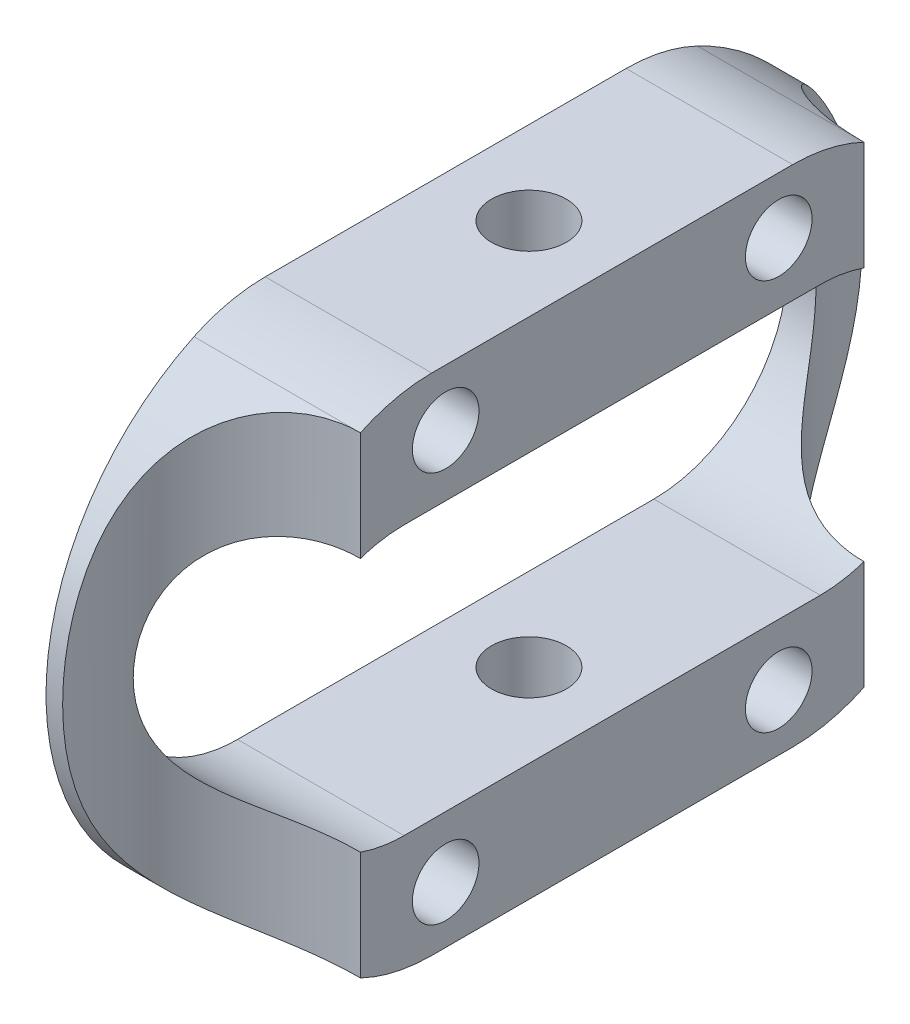
SolidWorks part; units mm, degrees
ref_plane "Płaszczyzna przednia" through (0, 0, 0) normal (0, 0, 1) x (1, 0, 0)
ref_plane "Płaszczyzna górna" through (0, 0, 0) normal (0, 1, 0) x (1, 0, 0)
ref_plane "Płaszczyzna prawa" through (0, 0, 0) normal (1, 0, 0) x (0, 0, -1)
sketch "Szkic1" plane through (0, 0, 0) normal (1, 0, 0) x (0, 0, -1)
  line L0 (25, -16.1572) -> (-25, -16.1572)
  line L1 (0, 16.1572) -> (0, -16.1572) construction
  line L2 (-41, 0) -> (41, 0) construction
  line L3 (25, 16.1572) -> (-25, 16.1572)
  line L4 (-25, -16.1572) -> (25, -16.1572)
  line L5 (-21.6718, -30.2948) -> (21.6718, -30.2948)
  line L6 (21.6718, 30.2948) -> (-21.6718, 30.2948)
  circle A0 centre (-20, 23.5) radius 4
  circle A1 centre (20, 23.5) radius 4
  circle A2 centre (-20, -23.5) radius 4
  circle A3 centre (20, -23.5) radius 4
  ellipse E0 centre (-25, 0) end of major axis (-25, 16.1572) minor radius 16 (-25, 16.1572) -> (-25, -16.1572) ccw
  ellipse E1 centre (25, 0) end of major axis (25, 16.1572) minor radius 16 (25, -16.1572) -> (25, 16.1572) ccw
  ellipse E2 centre (-21.6718, -10.0983) end of major axis (-21.6718, 10.0983) minor radius 20 (-30.2337, -28.3506) -> (-21.6718, -30.2948) ccw
  ellipse E3 centre (21.6718, -10.0983) end of major axis (21.6718, -30.2948) minor radius 20 (21.6718, -30.2948) -> (30.2337, -28.3506) ccw
  ellipse E4 centre (16.9348, 0) end of major axis (16.9348, -31.3705) minor radius 31.0652 (30.2337, -28.3506) -> (30.2337, 28.3506) ccw
  ellipse E5 centre (21.6718, 10.0983) end of major axis (21.6718, -10.0983) minor radius 20 (30.2337, 28.3506) -> (21.6718, 30.2948) ccw
  ellipse E6 centre (-21.6718, 10.0983) end of major axis (-21.6718, -10.0983) minor radius 20 (-21.6718, 30.2948) -> (-30.2337, 28.3506) ccw
  ellipse E7 centre (-16.9348, 0) end of major axis (-16.9348, -31.3705) minor radius 31.0652 (-30.2337, 28.3506) -> (-30.2337, -28.3506) ccw
  point P0 (-20, 23.5)
  point P2 (20, 23.5)
  point P3 (20, -23.5)
  point P11 (-20, -23.5)
  dimension "D1" = 23.5
  dimension "D2" = 20
  dimension "D3" = 1.6718
  dimension "D4" = 9
  dimension "D5" = 14.1304
  dimension "D6" = 16.9348
  dimension "D7" = 20
  dimension "D8" = 21.6718
  dimension "D9" = 25
  dimension "D10" = 9
  dimension "D18" = 23.5
extrude "Dodanie-wyciągnięcie1" add sketch "Szkic1" along normal blind 20 contours E6 E7 E2 L5 E3 E4 E5 L6 A0 A1 A2 A3 E1 L0 E0 L3
sketch "Szkic2" plane through (0, -30.2948, 0) normal (0, -1, 0) x (1, 0, 0)
  line L1 (0, 0) -> (20, 0) construction
  line L2 (20, 21.6718) -> (20, -21.6718) construction
  line L8 (20, 48) -> (0, 48) construction
  line L11 (2, 48) -> (2, 49.8717)
  line L12 (2, 49.8717) -> (22.128, 49.8717)
  line L13 (22.128, 49.8717) -> (22.128, 30.2337)
  line L14 (22.128, 30.2337) -> (20, 30.2337)
  line L15 (22.128, -30.2337) -> (20, -30.2337)
  line L16 (22.128, -49.8717) -> (22.128, -30.2337)
  line L17 (2, -49.8717) -> (22.128, -49.8717)
  line L18 (2, -48) -> (2, -49.8717)
  arc A2 (20, 30.2337) -> (2, 48) centre (19.8831, 48.1169) cw
  arc A4 (20, -30.2337) -> (2, -48) centre (19.8831, -48.1169) ccw
extrude "Wytnij-wyciągnięcie4" cut sketch "Szkic2" against normal through all both and the other way through all
hole_wizard "Pogłębienie stożkowe pod M8 Śrubę z łbem soczewkowym1" positions "Szkic 3D1" profile "Szkic4" countersink size "M8" standard "ISO" end condition through all
sketch3d "Szkic 3D1"
  line L0 (0, -30.2948, 21.6718) -> (0, -30.2948, -21.6718) construction
  line L1 (0, 0, 0) -> (20.0884, 0, 0) construction
  point P0 (10, -30.2948, 0)
  dimension "D1" = 10
sketch "Szkic4" plane through (10, -30.2948, 0) normal (1, 0, 0) x (0, 0, -1)
  line L0 (0, 0) -> (0, 60.5897)
  line L1 (0, 60.5897) -> (4.5, 60.5897)
  line L2 (4.5, 60.5897) -> (4.5, 4.15)
  line L3 (4.5, 4.15) -> (8.65, 0)
  line L5 (8.65, 0) -> (0, 0)
  line L6 (-4.5, 4.15) -> (-8.65, 0) construction
  line L11 (0, -6.35) -> (0, 107.95) construction
  dimension "Średnica otworu na wylot" = 9
  dimension "Głębokość otworu na wylot" = 60.5897
  dimension "Średnica zewnętrznego pogłębienia stożkowego" = 17.3
  dimension "Kąt zewnętrznego pogłębienia stożkowego" = 90
